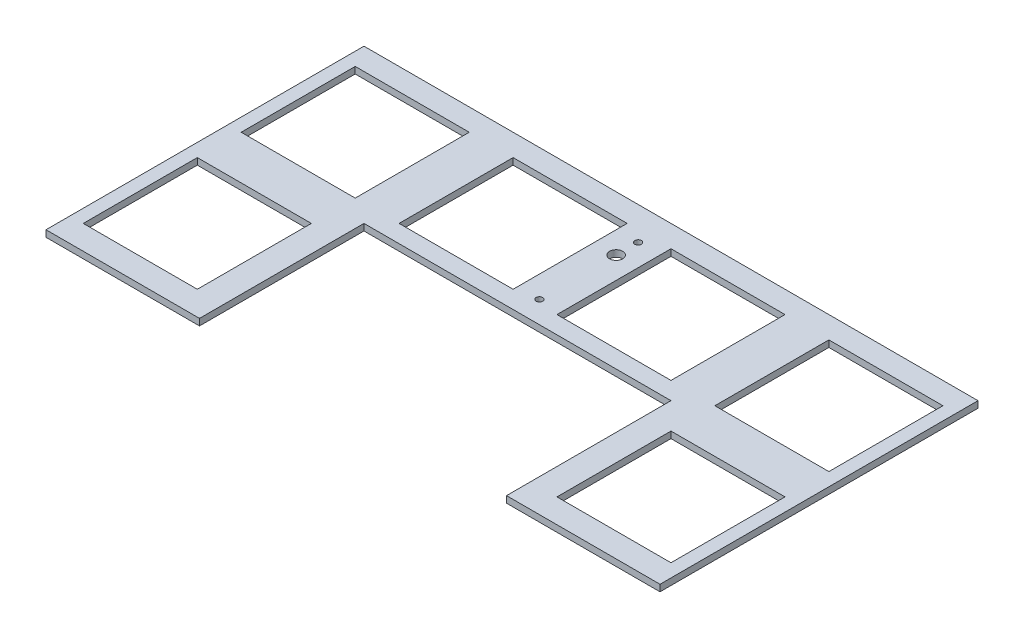
SolidWorks part; units mm, degrees
ref_plane "前视基准面" through (0, 0, 0) normal (0, 0, 1) x (1, 0, 0)
ref_plane "上视基准面" through (0, 0, 0) normal (0, 1, 0) x (1, 0, 0)
ref_plane "右视基准面" through (0, 0, 0) normal (1, 0, 0) x (0, 0, -1)
sketch "草图1" plane through (0, 0, 0) normal (0, 1, 0) x (1, 0, 0)
  line L0 (-140, -50) -> (-70, -50)
  line L2 (-140, -50) -> (-140, 95)
  line L3 (-140, 95) -> (140, 95)
  line L4 (140, -50) -> (140, 95)
  line L5 (10, 85) -> (62, 85)
  line L6 (10, 85) -> (10, 33)
  line L7 (10, 33) -> (62, 33)
  line L8 (62, 85) -> (62, 33)
  line L9 (-10, 33) -> (-62, 33)
  line L10 (-10, 33) -> (-10, 85)
  line L11 (-10, 85) -> (-62, 85)
  line L12 (-62, 33) -> (-62, 85)
  line L13 (-82, 33) -> (-134, 33)
  line L14 (-82, 33) -> (-82, 85)
  line L15 (-82, 85) -> (-134, 85)
  line L16 (-134, 33) -> (-134, 85)
  line L17 (82, 33) -> (134, 33)
  line L18 (82, 33) -> (82, 85)
  line L19 (82, 85) -> (134, 85)
  line L20 (134, 33) -> (134, 85)
  line L21 (-134, 13) -> (-82, 13)
  line L22 (-134, 13) -> (-134, -39)
  line L23 (-134, -39) -> (-82, -39)
  line L24 (-82, 13) -> (-82, -39)
  line L25 (82, 13) -> (134, 13)
  line L26 (82, 13) -> (82, -39)
  line L27 (82, -39) -> (134, -39)
  line L28 (134, 13) -> (134, -39)
  line L29 (-70, -50) -> (-70, 25)
  line L30 (-70, 25) -> (70, 25)
  line L31 (70, 25) -> (70, -50)
  line L32 (70, -50) -> (140, -50)
  circle A0 centre (0, 80) radius 1.5
  circle A1 centre (0, 35) radius 1.5
  circle A2 centre (0, 70) radius 3
  point P40 (0, 0)
  dimension "D1" = 52
  dimension "D2" = 52
  dimension "D3" = 10
  dimension "D4" = 10
  dimension "D5" = 52
  dimension "D6" = 52
  dimension "D7" = 10
  dimension "D8" = 20
  dimension "D9" = 52
  dimension "D10" = 52
  dimension "D11" = 20
  dimension "D12" = 52
  dimension "D13" = 20
  dimension "D14" = 52
  dimension "D15" = 52
  dimension "D16" = 20
extrude "凸台-拉伸1" add sketch "草图1" along normal blind 3
